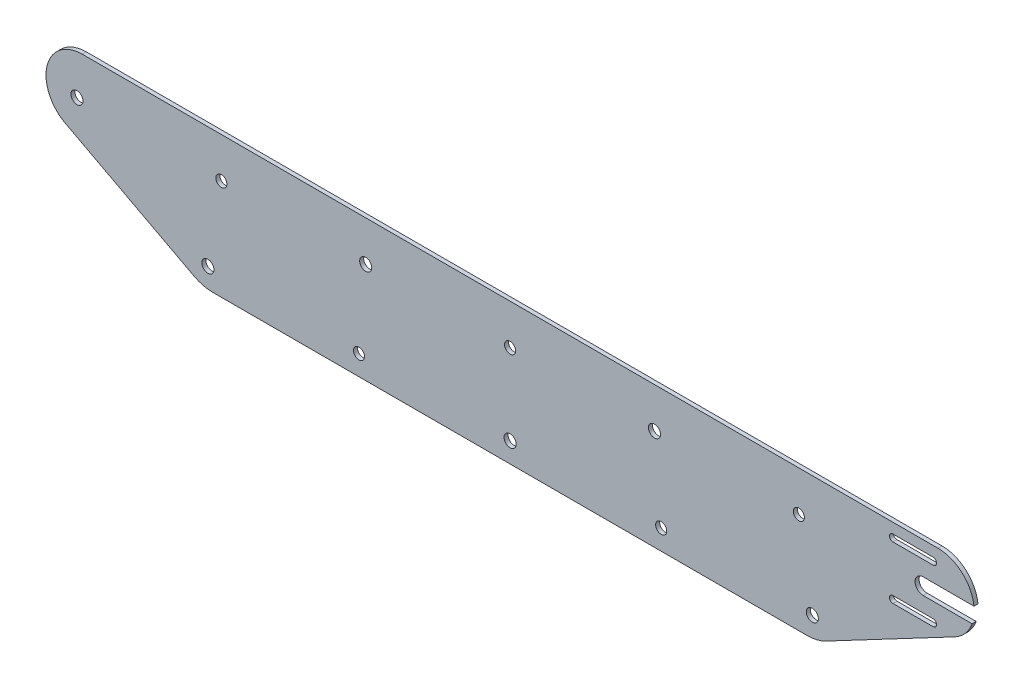
SolidWorks part; units mm, degrees
ref_plane "Plan de face" through (0, 0, 0) normal (0, 0, 1) x (1, 0, 0)
ref_plane "Plan de dessus" through (0, 0, 0) normal (0, 1, 0) x (1, 0, 0)
ref_plane "Plan de droite" through (0, 0, 0) normal (1, 0, 0) x (0, 0, -1)
sketch "Esquisse1" plane through (0, 0, 0) normal (0, 0, 1) x (1, 0, 0)
  line L0 (0, 0) -> (0, 122.747) construction
  line L1 (-215, -20) -> (215, -20) construction
  line L2 (-215, -20) -> (-215, 20) construction
  line L3 (-215, 20) -> (215, 20) construction
  line L4 (215, -20) -> (215, 20) construction
  line L5 (-215, -20) -> (215, 20) construction
  line L6 (-215, 20) -> (215, -20) construction
  line L7 (-1220, 0) -> (-150, 0) construction
  line L8 (-284.959, 40) -> (-150, 40)
  line L9 (150, 40) -> (284.959, 40)
  line L10 (150, 0) -> (150, -20) construction
  line L11 (150, -20) -> (-150, -20) construction
  line L12 (-150, 0) -> (-150, -20) construction
  line L13 (150, 0) -> (-150, -20) construction
  line L14 (150, -20) -> (-150, 0) construction
  line L15 (-284.959, 40) -> (-152.4795, -30)
  line L16 (-152.4795, -30) -> (152.4795, -30)
  line L17 (284.959, 40) -> (152.4795, -30)
  line L18 (-215, 20) -> (-71.6667, 20) construction
  line L19 (-71.6667, 20) -> (71.6667, 20) construction
  line L20 (71.6667, 20) -> (215, 20) construction
  line L21 (150, 0) -> (193.5165, 0) construction
  line L22 (150, 95) -> (-150, 95) construction
  line L23 (150, 95) -> (150, 40) construction
  line L24 (-150, 40) -> (150, 40)
  line L25 (-150, 95) -> (-150, 40) construction
  line L26 (150, 95) -> (-150, 0) construction
  line L27 (150, 0) -> (-150, 95) construction
  circle A0 centre (-215, 20) radius 3
  circle A1 centre (-150, -20) radius 3
  circle A2 centre (150, -20) radius 3
  circle A3 centre (215, 20) radius 3
  circle A4 centre (0, -20) radius 3
  circle A5 centre (-71.6667, 20) radius 3
  circle A6 centre (71.6667, 20) radius 3
  circle A7 centre (0, 78.03) radius 3 construction
  point P0 (0, 0)
  point P8 (0, -10)
  point P20 (0, 47.5)
  point P21 (0, -30)
  point P31 (0, 47.5)
  dimension "D8" = 6
  dimension "D10" = 58.03
  dimension "D1" = 430
  dimension "D2" = 40
  dimension "D3" = 300
  dimension "D4" = 20
  dimension "D5" = 15
  dimension "D6" = 10
  dimension "D7" = 10
  dimension "D9" = 55
extrude "Boss.-Extru.1" add sketch "Esquisse1" along normal blind 2
fillet "Congé1" radius 18 2 edges at (-284.959, 40, 1) (284.959, 40, 1)
fillet "Congé2" radius 20 2 edges at (-152.4795, -30, 1) (152.4795, -30, 1)
hole_wizard "Dégagement M31" positions "Esquisse3" profile "Esquisse2" hole size "M3" standard "Ansi Metric" end condition through all
sketch "Esquisse3" plane through (0, 0, 0) normal (0, 0, -1) x (-1, 0, 0)
  line L0 (-215, 12.5) -> (-215, 20)
  line L1 (-200, 6.7712) -> (-200, 33.2288)
  circle A0 centre (-215, 20) radius 7.5
  circle A1 centre (-215, 20) radius 20
  point P0 (-200, 33.2288)
  point P29 (-200, 6.7712)
  dimension "D2" = 15
  dimension "D3" = 40
  dimension "D1" = 15
sketch "Esquisse2" plane through (200, 33.2288, 0) normal (1, 0, 0) x (0, 1, 0)
  line L0 (0, 0) -> (0, 2)
  line L1 (0, 2) -> (1.7, 2)
  line L2 (1.7, 2) -> (1.7, 0)
  line L5 (1.7, 0) -> (0, 0)
  line L11 (0, -6.35) -> (0, 107.95) construction
  dimension "Diamètre du perçage jusqu'au prochain" = 3.4
  dimension "Profondeur du perçage jusqu'au prochain" = 2
sketch "Esquisse4" plane through (0, 0, 0) normal (0, 0, -1) x (-1, 0, 0)
  line L0 (-215, 24) -> (-230.2521, 24)
  line L1 (-215, 24) -> (-205, 24)
  line L2 (-215, 16) -> (-205, 16)
  line L3 (-215, 16) -> (-229.3341, 16)
  line L4 (-147.5205, -30) -> (147.5205, -30)
  line L5 (156.8641, -27.6833) -> (220.7728, 6.0851)
  line L6 (212.3636, 40) -> (-212.3636, 40)
  line L7 (-220.7728, 6.0851) -> (-156.8641, -27.6833)
  line L8 (-147.5205, -30) -> (147.5205, -30)
  line L9 (156.8641, -27.6833) -> (220.7728, 6.0851)
  line L10 (212.3636, 40) -> (-212.3636, 40)
  line L11 (-220.7728, 6.0851) -> (-156.8641, -27.6833)
  line L12 (-215, 16) -> (-215, 24)
  line L13 (-200, 34.9288) -> (-210, 34.9288)
  line L14 (-200, 34.9288) -> (-200, 31.5288)
  line L15 (-210, 31.5288) -> (-200, 31.5288)
  line L16 (-200, 31.5288) -> (-190, 31.5288)
  line L17 (-200, 8.4712) -> (-210, 8.4712)
  line L18 (-190, 34.9288) -> (-200, 34.9288)
  line L19 (-200, 8.4712) -> (-200, 5.0712)
  line L20 (-210, 5.0712) -> (-200, 5.0712)
  line L21 (-200, 5.0712) -> (-190, 5.0712)
  line L22 (-190, 8.4712) -> (-200, 8.4712)
  line L23 (-175, 14.2) -> (-185, 14.2)
  line L24 (-175, 14.2) -> (-175, 10.8)
  line L25 (-185, 10.8) -> (-175, 10.8)
  line L26 (-175, 10.8) -> (-165, 10.8)
  line L27 (-165, 14.2) -> (-175, 14.2)
  line L28 (-185, 14.2) -> (-228.5858, 14.2)
  line L29 (-185, 10.8) -> (-226.4547, 10.8)
  arc A2 (-205, 24) -> (-205, 16) centre (-205, 20) cw
  circle A3 centre (-215, 20) radius 3 construction
  arc A4 (147.5205, -30) -> (156.8641, -27.6833) centre (147.5205, -10) ccw
  arc A5 (220.7728, 6.0851) -> (212.3636, 40) centre (212.3636, 22) ccw
  arc A6 (-212.3636, 40) -> (-220.7728, 6.0851) centre (-212.3636, 22) ccw
  arc A7 (-156.8641, -27.6833) -> (-147.5205, -30) centre (-147.5205, -10) ccw
  arc A8 (147.5205, -30) -> (156.8641, -27.6833) centre (147.5205, -10) ccw
  arc A9 (220.7728, 6.0851) -> (212.3636, 40) centre (212.3636, 22) ccw
  arc A10 (-212.3636, 40) -> (-220.7728, 6.0851) centre (-212.3636, 22) ccw
  arc A11 (-156.8641, -27.6833) -> (-147.5205, -30) centre (-147.5205, -10) ccw
  circle A12 centre (-200, 33.2288) radius 1.7 construction
  circle A13 centre (-200, 33.2288) radius 1.7 construction
  arc A14 (-190, 34.9288) -> (-190, 31.5288) centre (-190, 33.2288) cw
  arc A15 (-210, 34.9288) -> (-210, 31.5288) centre (-210, 33.2288) ccw
  arc A16 (-190, 8.4712) -> (-190, 5.0712) centre (-190, 6.7712) cw
  arc A17 (-210, 8.4712) -> (-210, 5.0712) centre (-210, 6.7712) ccw
  arc A18 (-165, 14.2) -> (-165, 10.8) centre (-165, 12.5) cw
  circle A20 centre (-200, 6.7712) radius 1.7 construction
  point P17 (-215, 20)
  point P32 (-200, 33.2288)
  point P41 (-200, 6.7712)
  point P52 (-175, 12.5)
  dimension "D2" = 10
  dimension "D3" = 8
  dimension "D4" = 10
  dimension "D5" = 10
  dimension "D6" = 10
  dimension "D1" = 0
extrude "Enlèv. mat.-Extru.1" cut sketch "Esquisse4" against normal through all contours L3 A15 L0 A6 | A2 L1 A15 L2 | A14 L18 L2 L16 | L13 A15 L15 L2 | L17 A17 L20 L4 | A16 L22 L4 L21
hole_wizard "Dégagement M51" positions "Esquisse6" profile "Esquisse5" hole size "M5" standard "Ansi Metric" end condition through all
sketch "Esquisse6" plane through (0, 0, 0) normal (0, 0, -1) x (-1, 0, 0)
  line L0 (215, 20) -> (31.0935, 20) construction
  line L2 (215, 20) -> (143.3333, 20)
  line L4 (143.3333, 20) -> (71.6667, 20)
  line L5 (71.6667, 20) -> (0, 20)
  line L6 (0, 20) -> (-71.6667, 20)
  line L7 (-71.6667, 20) -> (-143.3333, 20)
  circle A2 centre (215, 20) radius 3
  circle A3 centre (215, 20) radius 3 construction
  circle A4 centre (-71.6667, 20) radius 3
  circle A5 centre (-71.6667, 20) radius 3 construction
  point P0 (143.3333, 20)
  point P2 (0, 20)
  point P37 (-143.3333, 20)
sketch "Esquisse5" plane through (-143.3333, 20, 0) normal (1, 0, 0) x (0, 1, 0)
  line L0 (0, 0) -> (0, 2)
  line L1 (0, 2) -> (2.75, 2)
  line L2 (2.75, 2) -> (2.75, 0)
  line L5 (2.75, 0) -> (0, 0)
  line L11 (0, -6.35) -> (0, 107.95) construction
  dimension "Diamètre du perçage jusqu'au prochain" = 5.5
  dimension "Profondeur du perçage jusqu'au prochain" = 2
hole_wizard "Dégagement M52" positions "Esquisse8" profile "Esquisse7" hole size "M5" standard "Ansi Metric" end condition through all
sketch "Esquisse8" plane through (0, 0, 2) normal (0, 0, 1) x (1, 0, 0)
  line L0 (-150, -20) -> (-75, -20)
  line L1 (-75, -20) -> (0, -20)
  line L2 (0, -20) -> (75, -20)
  line L3 (75, -20) -> (150, -20)
  point P0 (-75, -20)
  point P2 (75, -20)
sketch "Esquisse7" plane through (-75, -20, 2) normal (1, 0, 0) x (0, -1, 0)
  line L0 (0, 0) -> (0, 2)
  line L1 (0, 2) -> (2.75, 2)
  line L2 (2.75, 2) -> (2.75, 0)
  line L5 (2.75, 0) -> (0, 0)
  line L11 (0, -6.35) -> (0, 107.95) construction
  dimension "Diamètre du perçage jusqu'au prochain" = 5.5
  dimension "Profondeur du perçage jusqu'au prochain" = 2
